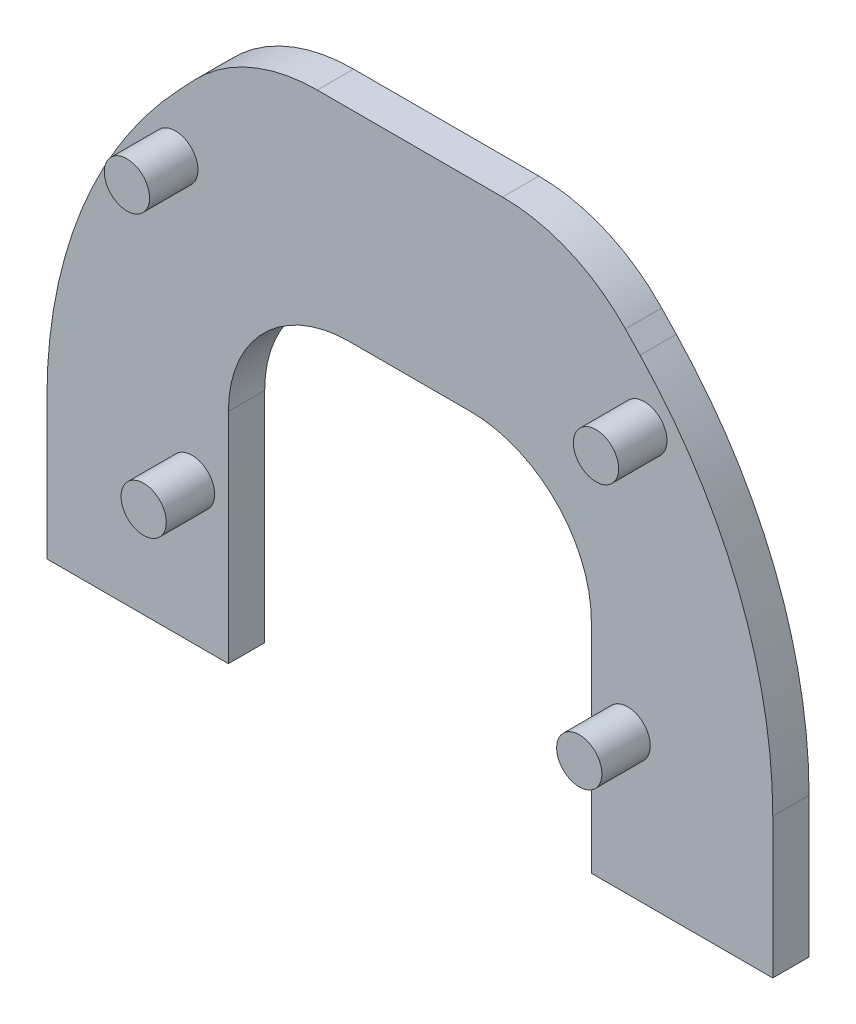
SolidWorks part; units mm, degrees
ref_plane "Front Plane" through (0, 0, 0) normal (0, 0, 1) x (1, 0, 0)
ref_plane "Top Plane" through (0, 0, 0) normal (0, 1, 0) x (1, 0, 0)
ref_plane "Right Plane" through (0, 0, 0) normal (1, 0, 0) x (0, 0, -1)
sketch "Sketch1" plane through (0, 0, 0) normal (0, 0, 1) x (-1, 0, 0)
  line L1 (22.6285, -66.4321) -> (24.1656, -64.8109)
  line L3 (38.1, -29.86) -> (38.1, -15.1587)
  line L5 (19.05, -15.1587) -> (19.05, -38.1)
  line L7 (6.35, -50.8) -> (-6.35, -50.8)
  line L9 (-19.05, -38.1) -> (-19.05, -15.1587)
  line L11 (-38.1, -15.1587) -> (-38.1, -29.86)
  line L13 (-24.1656, -64.8109) -> (-22.6285, -66.4321)
  line L14 (38.1, -15.1587) -> (19.05, -15.1587)
  line L15 (9.7256, -71.9793) -> (-9.7256, -71.9793)
  line L16 (-19.05, -15.1587) -> (-38.1, -15.1587)
  arc A1 (9.7256, -71.9793) -> (22.6285, -66.4321) centre (9.7256, -54.1993) ccw
  arc A3 (24.1656, -64.8109) -> (38.1, -29.86) centre (-12.7, -29.86) ccw
  arc A5 (6.35, -50.8) -> (19.05, -38.1) centre (6.35, -38.1) ccw
  arc A7 (-19.05, -38.1) -> (-6.35, -50.8) centre (-6.35, -38.1) ccw
  arc A9 (-38.1, -29.86) -> (-24.1656, -64.8109) centre (12.7, -29.86) ccw
  arc A11 (-22.6285, -66.4321) -> (-9.7256, -71.9793) centre (-9.7256, -54.1993) ccw
extrude "Boss-Extrude1" add sketch "Sketch1" along normal blind 3.81 contours A1 L1 A3 L3 L14 L5 A5 L7 A7 L9 L16 L11 A9 L13 A11 L15
sketch "Sketch3" plane through (0, 0, 0) normal (0, 0, 1) x (1, 0, 0)
  circle A0 centre (-24.6225, 58.4453) radius 2.3749
  circle A2 centre (-22.8654, 29.8267) radius 2.3749
  point P2 (0, 0)
  dimension "D1" = 4.7498
  dimension "D4" = 4.7498
extrude "Boss-Extrude2" add sketch "Sketch3" along normal blind 8.89 contours A0 | A2
mirror "Mirror1" about plane through (0, 0, 0) normal (1, 0, 0) of "Boss-Extrude2"
